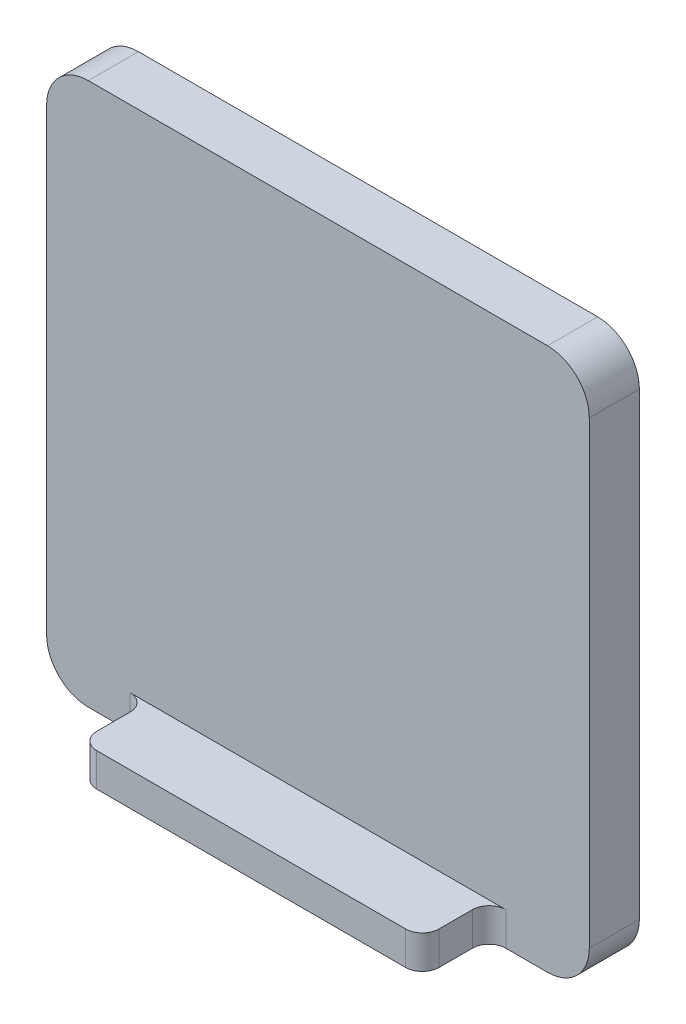
SolidWorks part; units mm, degrees
ref_plane "Front Plane" through (0, 0, 0) normal (0, 0, 1) x (1, 0, 0)
ref_plane "Top Plane" through (0, 0, 0) normal (0, 1, 0) x (1, 0, 0)
ref_plane "Right Plane" through (0, 0, 0) normal (1, 0, 0) x (0, 0, -1)
sketch "Sketch1" plane through (0, 0, 0) normal (0, 0, 1) x (1, 0, 0)
  line L1 (-32.5, 32.5) -> (32.5, 32.5)
  line L2 (-32.5, 32.5) -> (-32.5, -32.5)
  line L3 (-32.5, -32.5) -> (32.5, -32.5)
  line L4 (32.5, 32.5) -> (32.5, -32.5)
  line L5 (-32.5, 32.5) -> (32.5, -32.5) construction
  line L6 (-32.5, -32.5) -> (32.5, 32.5) construction
  point P0 (0, 0)
  dimension "D1" = 65
  dimension "D2" = 65
extrude "Boss-Extrude1" add sketch "Sketch1" along normal blind 6
fillet "Fillet1" radius 5 4 edges at (32.5, -32.5, 3) (-32.5, -32.5, 3) (32.5, 32.5, 3) (-32.5, 32.5, 3)
sketch "Sketch2" plane through (0, 0, 6) normal (0, 0, 1) x (1, 0, 0)
  line L0 (-27.5, -32.5) -> (27.5, -32.5) construction
  line L1 (-20.5, -32.5) -> (20.5, -32.5)
  line L2 (-20.5, -32.5) -> (-20.5, -28.5)
  line L3 (-20.5, -28.5) -> (20.5, -28.5)
  line L4 (20.5, -32.5) -> (20.5, -28.5)
  line L5 (0, 0) -> (0, -28.5) construction
  dimension "D1" = 41
  dimension "D2" = 4
extrude "Boss-Extrude2" add sketch "Sketch2" along normal blind 8
fillet "Fillet2" radius 2 4 edges at (20.5, -30.5, 6) (20.5, -30.5, 14) (-20.5, -30.5, 14) (-20.5, -30.5, 6)
